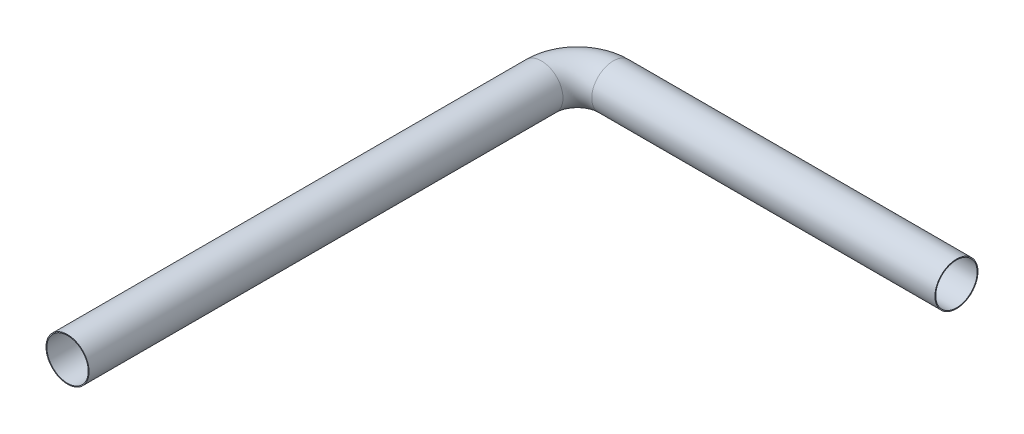
SolidWorks part; units mm, degrees
ref_plane "Front Plane" through (0, 0, 0) normal (0, 0, 1) x (1, 0, 0)
ref_plane "Top Plane" through (0, 0, 0) normal (0, 1, 0) x (1, 0, 0)
ref_plane "Right Plane" through (0, 0, 0) normal (1, 0, 0) x (0, 0, -1)
sketch "Sketch1" plane through (0, 0, 0) normal (0, 0, 1) x (1, 0, 0)
  circle A0 centre (0, 0) radius 30
  circle A1 centre (0, 0) radius 28.8
  dimension "D1" = 60
  dimension "D2" = 1.2
sketch "Sketch2" plane through (0, 0, 0) normal (0, 1, 0) x (1, 0, 0)
  line L0 (0, 0) -> (0, 660)
  line L1 (-28.8, 0) -> (28.8, 0) construction
  line L2 (50, 710) -> (527.9584, 710)
  line L3 (527.9584, 695.0607) -> (527.9584, 719.655) construction
  line L7 (527.9584, 665.5792) -> (527.9584, 755.5792) construction
  arc A0 (0, 660) -> (50, 710) centre (50, 660) cw
  point P7 (0, 710)
  dimension "D3" = 50
  dimension "D1" = 710
sweep "Sweep1" add profiles "Sketch1" path "Sketch2"
